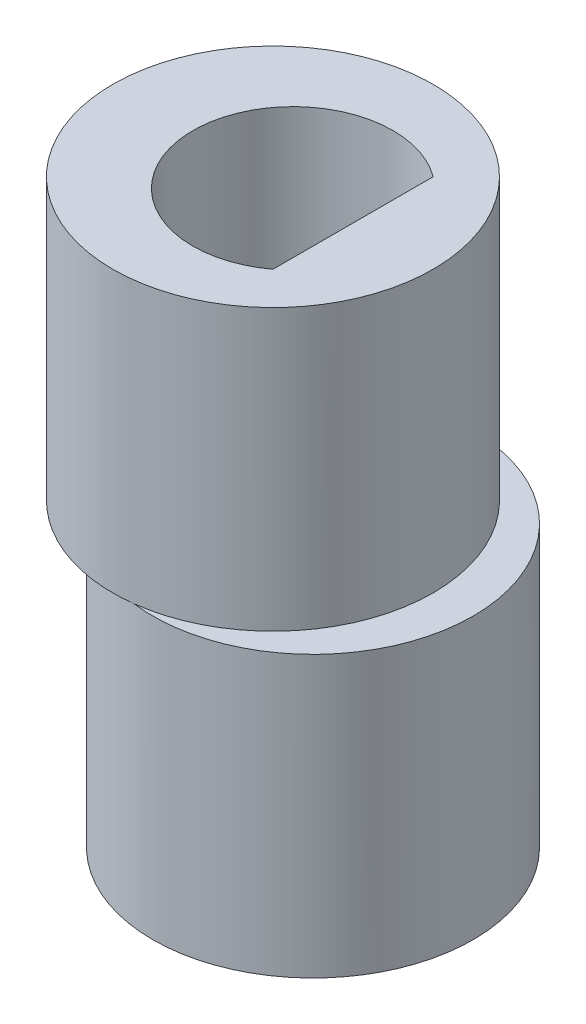
SolidWorks part; units mm, degrees
ref_plane "Front Plane" through (0, 0, 0) normal (0, 0, 1) x (1, 0, 0)
ref_plane "Top Plane" through (0, 0, 0) normal (0, 1, 0) x (1, 0, 0)
ref_plane "Right Plane" through (0, 0, 0) normal (1, 0, 0) x (0, 0, -1)
sketch "Sketch1" plane through (0, 0, 0) normal (0, 1, 0) x (1, 0, 0)
  line L0 (0, 0) -> (0.5, 0) construction
  circle A0 centre (0, 0) radius 2.5
  circle A1 centre (0.5, 0) radius 4
  dimension "D1" = 5
  dimension "D3" = 8
  dimension "D2" = 0.5
extrude "Boss-Extrude1" add sketch "Sketch1" along normal blind 7
sketch "Sketch2" plane through (0, 7, 0) normal (0, 1, 0) x (1, 0, 0)
  line L0 (0, 0) -> (-0.5, 0) construction
  circle A0 centre (0, 0) radius 2.5 construction
  circle A1 centre (0, 0) radius 2.5
  circle A2 centre (-0.5, 0) radius 4
  dimension "D2" = 8
extrude "Boss-Extrude2" add sketch "Sketch2" along normal blind 7
sketch "Sketch3" plane through (0, 14, 0) normal (0, 1, 0) x (1, 0, 0)
  line L0 (1.5, 2) -> (1.5, -2)
  circle A0 centre (0, 0) radius 2.5 construction
  arc A1 (1.5, -2) -> (1.5, 2) centre (0, 0) ccw
  dimension "D1" = 1.5
extrude "Boss-Extrude3" add sketch "Sketch3" against normal through all
equation "\"D2@Sketch1\"=\"eccentricity\""
equation "\"D1@Sketch2\"=\"eccentricity\""
